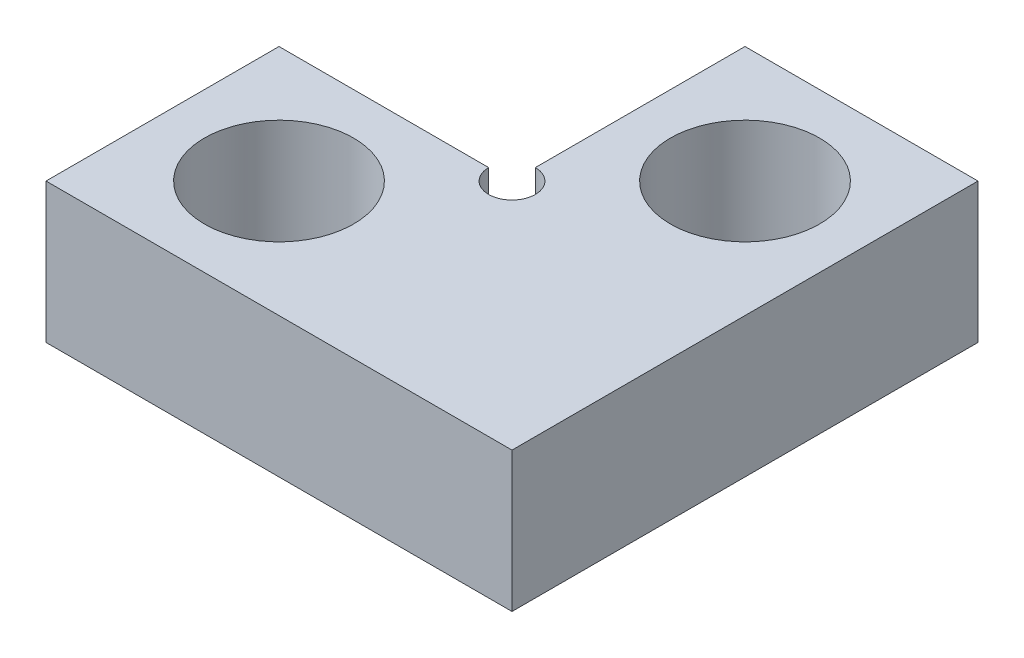
SolidWorks part; units mm, degrees
ref_plane "Alzado" through (0, 0, 0) normal (0, 0, 1) x (1, 0, 0)
ref_plane "Planta" through (0, 0, 0) normal (0, 1, 0) x (1, 0, 0)
ref_plane "Vista lateral" through (0, 0, 0) normal (1, 0, 0) x (0, 0, -1)
sketch "Croquis1" plane through (0, 0, 0) normal (0, 1, 0) x (1, 0, 0)
  line L0 (-5, 0) -> (0, 0)
  line L1 (0, 0) -> (0, 5)
  line L2 (0, 5) -> (5, 5)
  line L3 (5, 5) -> (5, -5)
  line L4 (5, -5) -> (-5, -5)
  line L5 (-5, -5) -> (-5, 0)
  circle A0 centre (2.5, 2.5) radius 1.6
  circle A1 centre (-2.5, -2.5) radius 1.6
  arc A2 (0, 0.5) -> (-0.5, 0) centre (0, 0) cw
  point P11 (0.3536, -0.3536)
  point P12 (-5, -2.5)
  point P13 (0, 0)
  point P14 (2.5, 5)
  point P15 (0, 0)
  point P16 (-2.5, 0)
  point P17 (-0.7852, 0)
  point P18 (0, 2.5)
  point P22 (0, 0)
  dimension "D5" = 3.2
  dimension "D1" = 10
  dimension "D2" = 10
  dimension "D3" = 5
  dimension "D4" = 5
  dimension "D6" = 0.5
extrude "Saliente-Extruir1" add sketch "Croquis1" along normal blind 3 contours L1 A2 L0 L5 L4 L3 L2 A1 A0
